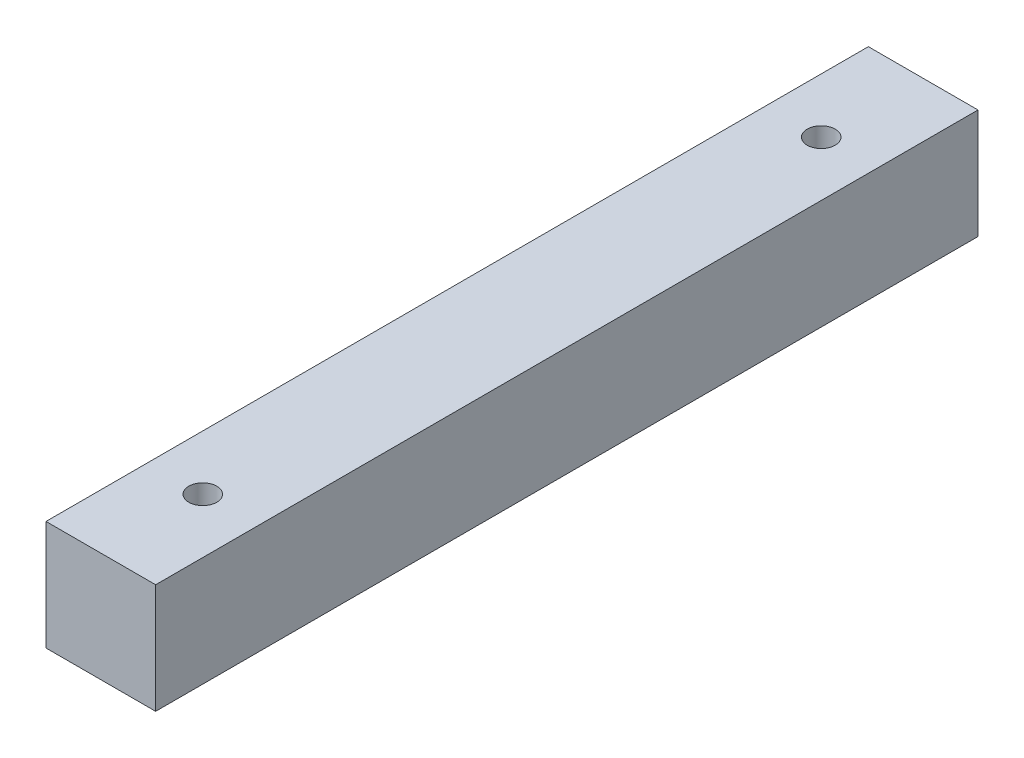
SolidWorks part; units mm, degrees
ref_plane "Front" through (0, 0, 0) normal (0, 0, 1) x (1, 0, 0)
ref_plane "Top" through (0, 0, 0) normal (0, 1, 0) x (1, 0, 0)
ref_plane "Right" through (0, 0, 0) normal (1, 0, 0) x (0, 0, -1)
sketch "草图1" plane through (0, 0, 0) normal (0, 0, 1) x (1, 0, 0)
  line L1 (-10, 10) -> (10, 10)
  line L2 (-10, 10) -> (-10, -10)
  line L3 (-10, -10) -> (10, -10)
  line L4 (10, 10) -> (10, -10)
  line L5 (-10, 10) -> (10, -10) construction
  line L6 (-10, -10) -> (10, 10) construction
  point P0 (0, 0)
  dimension "D1" = 20
  dimension "D2" = 20
extrude "凸台-拉伸1" add sketch "草图1" along normal blind 150
sketch "草图2" plane through (0, 10, 0) normal (0, 1, 0) x (1, 0, 0)
  circle A0 centre (0, -131.4) radius 2.55
  circle A1 centre (0, -18.6) radius 2.55
  dimension "D1" = 5.1
  dimension "D2" = 5.1
extrude "切除-拉伸1" cut sketch "草图2" against normal blind 43
